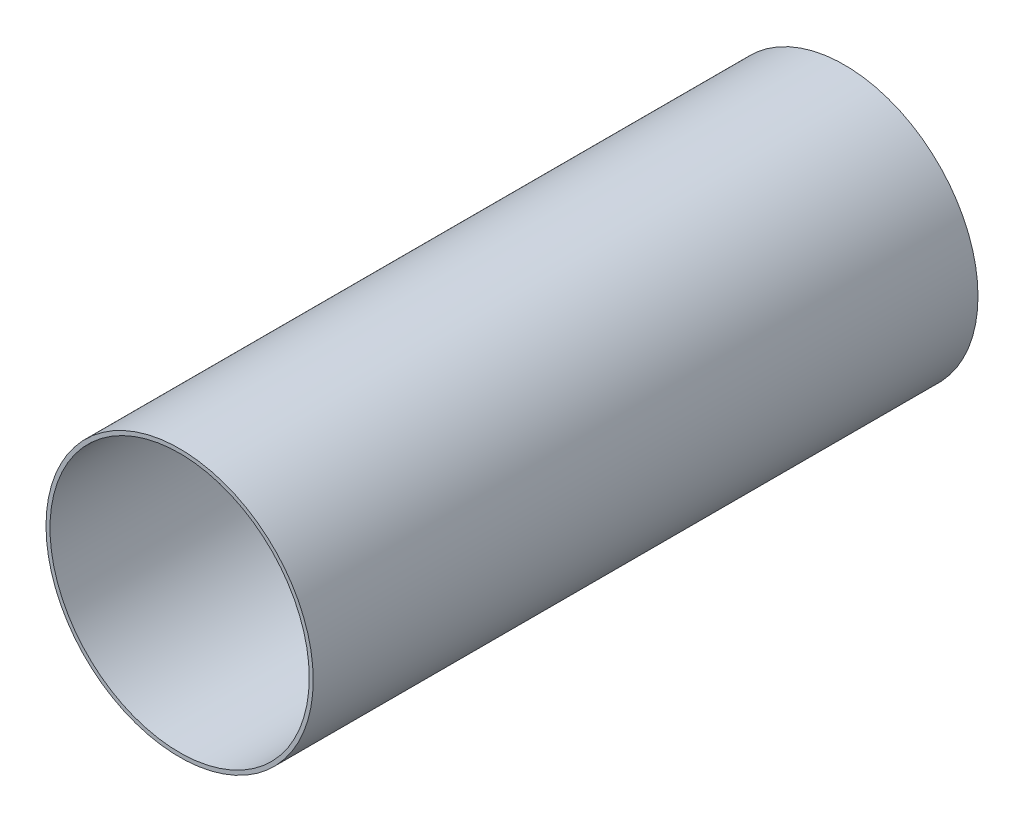
SolidWorks part; units mm, degrees
material "Wound G12 Fiberglass"
ref_plane "Front Plane" through (0, 0, 0) normal (0, 0, 1) x (1, 0, 0)
ref_plane "Top Plane" through (0, 0, 0) normal (0, 1, 0) x (1, 0, 0)
ref_plane "Right Plane" through (0, 0, 0) normal (1, 0, 0) x (0, 0, -1)
sketch "Sketch1" plane through (0, 0, 0) normal (0, 0, 1) x (1, 0, 0)
  circle A0 centre (0, 0) radius 49.53
  circle A1 centre (0, 0) radius 51.054
  dimension "D1" = 102.108
  dimension "D2" = 99.06
extrude "Boss-Extrude1" add sketch "Sketch1" along normal blind 254
